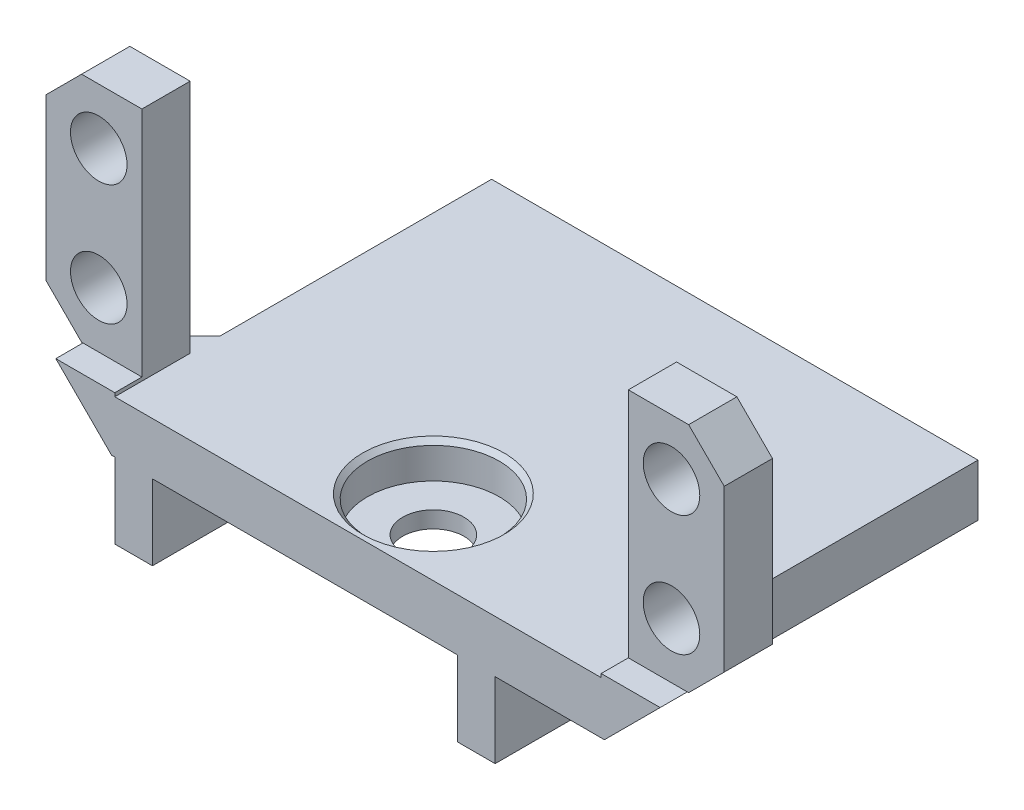
SolidWorks part; units mm, degrees
ref_plane "Front Plane" through (0, 0, 0) normal (0, 0, 1) x (1, 0, 0)
ref_plane "Top Plane" through (0, 0, 0) normal (0, 1, 0) x (1, 0, 0)
ref_plane "Right Plane" through (0, 0, 0) normal (1, 0, 0) x (0, 0, -1)
sketch "Sketch1" plane through (0, 0, 0) normal (0, 0, 1) x (1, 0, 0)
  line L0 (-17.4625, -10.541) -> (17.4625, -10.541) construction
  line L1 (17.4625, -21.209) -> (-17.4625, -21.209)
  line L2 (17.4625, -21.209) -> (17.4625, 1.651)
  line L3 (17.4625, 21.209) -> (-17.4625, 21.209)
  line L4 (-17.4625, -21.209) -> (-17.4625, 1.651)
  line L5 (17.4625, -21.209) -> (-17.4625, 21.209) construction
  line L6 (17.4625, 21.209) -> (-17.4625, -21.209) construction
  line L7 (0, 21.209) -> (0, -21.209) construction
  line L8 (-17.4625, 1.651) -> (17.4625, 1.651) construction
  line L9 (-17.4625, 6.35) -> (17.4625, 6.35) construction
  line L10 (-17.4625, 11.43) -> (17.4625, 11.43) construction
  line L11 (-17.4625, 11.43) -> (-17.4625, 1.651) construction
  line L12 (-17.4625, 5.4539) -> (-17.4625, 6.35)
  line L13 (28.575, 1.651) -> (17.4625, 1.651)
  line L14 (28.575, 1.651) -> (28.575, 21.209)
  line L15 (28.575, 21.209) -> (-28.575, 21.209)
  line L16 (-28.575, 1.651) -> (-28.575, 21.209)
  line L17 (28.575, 1.651) -> (-28.575, 21.209) construction
  line L18 (28.575, 21.209) -> (-28.575, 1.651) construction
  line L19 (17.4625, 5.4539) -> (17.4625, 6.35)
  line L20 (1.3594, 1.651) -> (-1.3594, 1.651)
  line L21 (-17.4625, 1.651) -> (-28.575, 1.651)
  circle A0 centre (-9.525, -10.541) radius 3.475
  circle A1 centre (9.525, -10.541) radius 3.475
  circle A2 centre (-24.13, 6.35) radius 2.3828
  circle A3 centre (-24.13, 16.51) radius 2.3828
  circle A4 centre (24.13, 16.51) radius 2.3828
  circle A5 centre (24.13, 6.35) radius 2.3828
  point P0 (0, 0)
  point P28 (0, 11.43)
  dimension "D4" = 9.525
  dimension "D7" = 9.779
  dimension "D1" = 34.925
  dimension "D2" = 42.418
  dimension "D3" = 10.668
  dimension "D5" = 22.86
  dimension "D6" = 4.699
  dimension "D8" = 24.13
  dimension "D9" = 57.15
extrude "Boss-Extrude1" add sketch "Sketch1" along normal blind 6.35
chamfer "Chamfer1" distance 3 angle 45 6 edges at (28.575, 21.209, 3.175) (28.575, 1.651, 3.175) (-28.575, 1.651, 3.175) (-28.575, 21.209, 3.175) (-17.4625, -21.209, 3.175) (17.4625, -21.209, 3.175)
chamfer "Chamfer2" distance 8 angle 45 2 edges at (-17.4625, 1.651, 3.175) (17.4625, 1.651, 3.175)
sketch "Sketch3" plane through (0, 0, 6.35) normal (0, 0, 1) x (1, 0, 0)
  line L0 (-25.4625, 1.651) -> (25.4625, 1.651)
  line L16 (-17.4625, -6.349) -> (-17.4625, -18.209)
  line L18 (-14.4625, -21.209) -> (14.4625, -21.209)
  line L19 (-17.4625, -18.209) -> (-14.4625, -21.209)
  line L20 (17.4625, -18.209) -> (17.4625, -6.349)
  line L21 (17.4625, -6.349) -> (25.4625, 1.651)
  line L22 (25.4625, 1.651) -> (25.575, 1.651)
  line L23 (25.575, 1.651) -> (28.575, 4.651)
  line L24 (28.575, 4.651) -> (28.575, 18.209)
  line L25 (28.575, 18.209) -> (25.575, 21.209)
  line L26 (25.575, 21.209) -> (-25.575, 21.209)
  line L27 (-25.575, 21.209) -> (-28.575, 18.209)
  line L28 (-28.575, 18.209) -> (-28.575, 4.651)
  line L29 (-28.575, 4.651) -> (-25.575, 1.651)
  line L30 (-25.575, 1.651) -> (-25.4625, 1.651)
  line L31 (-25.4625, 1.651) -> (-17.4625, -6.349)
  line L33 (14.4625, -21.209) -> (17.4625, -18.209)
  line L38 (25.4625, 1.651) -> (25.575, 1.651)
  line L39 (25.575, 1.651) -> (28.575, 4.651)
  line L40 (28.575, 4.651) -> (28.575, 18.209)
  line L41 (28.575, 18.209) -> (25.575, 21.209)
  line L42 (25.575, 21.209) -> (-25.575, 21.209)
  line L43 (-25.575, 21.209) -> (-28.575, 18.209)
  line L44 (-28.575, 18.209) -> (-28.575, 4.651)
  line L45 (-28.575, 4.651) -> (-25.575, 1.651)
  line L46 (-25.575, 1.651) -> (-25.4625, 1.651)
  dimension "D1" = 0
extrude "Cut-Extrude1" cut sketch "Sketch3" against normal blind 2.286
sketch "Sketch4" plane through (0, 0, 4.064) normal (0, 0, 1) x (1, 0, 0)
  line L0 (-28.575, 11.43) -> (28.575, 11.43) construction
  line L1 (-28.575, 18.209) -> (-28.575, 4.651) construction
  line L2 (28.575, 4.651) -> (28.575, 18.209) construction
  line L4 (20.493, 1.351) -> (-20.493, 1.351)
  line L5 (20.493, 1.351) -> (20.493, 21.509)
  line L6 (20.493, 21.509) -> (-20.493, 21.509)
  line L7 (-20.493, 1.351) -> (-20.493, 21.509)
  line L8 (20.493, 1.351) -> (-20.493, 21.509) construction
  line L9 (20.493, 21.509) -> (-20.493, 1.351) construction
  point P6 (0, 11.43)
  dimension "D1" = 40.986
  dimension "D2" = 20.158
extrude "Cut-Extrude2" cut sketch "Sketch4" against normal through all both and the other way through all
sketch "Sketch6" plane through (0, 0, 6.35) normal (0, 0, 1) x (1, 0, 0)
  line L1 (-30.4237, -3.0464) -> (26.5764, -3.0464)
  line L2 (-30.4237, -3.0464) -> (-30.4237, -22.0964)
  line L3 (-30.4237, -22.0964) -> (26.5764, -22.0964)
  line L4 (26.5764, -3.0464) -> (26.5764, -22.0964)
  dimension "D1" = 19.05
extrude "Cut-Extrude3" cut sketch "Sketch6" against normal through all
sketch "Sketch9" plane through (0, 0, 0) normal (0, 0, -1) x (-1, 0, 0)
  line L0 (-20.7651, -3.0464) -> (20.7651, -3.0464) construction
  line L1 (-20.493, 1.351) -> (20.493, 1.351)
  line L2 (-20.493, 1.351) -> (-20.493, -3.0464)
  line L3 (-20.493, -3.0464) -> (20.493, -3.0464)
  line L4 (20.493, 1.351) -> (20.493, -3.0464)
extrude "Boss-Extrude2" add sketch "Sketch9" along normal blind 25.4
chamfer "Chamfer3" distance 2.54 angle 45 2 edges
sketch "Sketch10" plane through (0, -3.0464, 0) normal (0, -1, 0) x (-1, 0, 0)
  line L0 (-20.493, 25.4) -> (20.493, 25.4) construction
  line L1 (20.493, -6.35) -> (17.318, -6.35)
  line L2 (20.493, -6.35) -> (20.493, 25.4)
  line L3 (20.493, 25.4) -> (17.318, 25.4)
  line L4 (17.318, -6.35) -> (17.318, 25.4)
  line L5 (-20.7651, -6.35) -> (20.7651, -6.35) construction
  line L6 (-8.382, -6.35) -> (-11.557, -6.35)
  line L7 (-8.382, -6.35) -> (-8.382, 25.4)
  line L8 (-8.382, 25.4) -> (-11.557, 25.4)
  line L9 (-11.557, -6.35) -> (-11.557, 25.4)
  dimension "D1" = 3.175
  dimension "D2" = 3.175
  dimension "D3" = 25.7
extrude "Boss-Extrude3" add sketch "Sketch10" along normal blind 6.35
sketch "Sketch11" plane through (0, 1.351, 0) normal (0, 1, 0) x (1, 0, 0)
  circle A0 centre (0, 0) radius 5.5562
  dimension "D1" = 11.1125
extrude "Cut-Extrude4" cut sketch "Sketch11" against normal blind 3
sketch "Sketch14" plane through (0, -1.649, 0) normal (0, 1, 0) x (1, 0, 0)
  circle A0 centre (0, 0) radius 2.5813
extrude "Cut-Extrude10" cut sketch "Sketch14" against normal blind 6.35
chamfer "Chamfer4" distance 0.4 angle 45 1 edges at (-5.5562, 1.351, 0)
